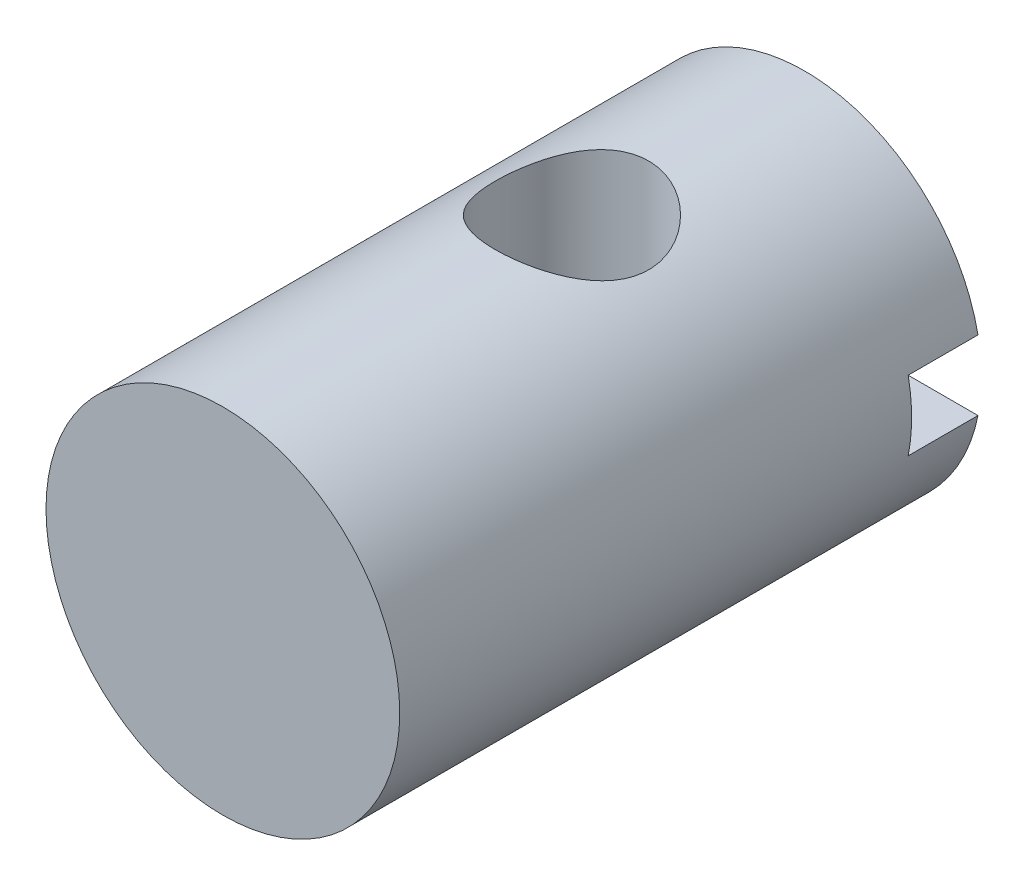
SolidWorks part; units mm, degrees
material "ABS"
ref_plane "Piano frontale" through (0, 0, 0) normal (0, 0, 1) x (1, 0, 0)
ref_plane "Piano superiore" through (0, 0, 0) normal (0, 1, 0) x (1, 0, 0)
ref_plane "Piano destro" through (0, 0, 0) normal (1, 0, 0) x (0, 0, -1)
ref_plane "Piano1" through (0, 0, 0) normal (0, -1, 0) x (1, 0, 0)
sketch "Schizzo1" plane through (0, 0, 0) normal (0, -1, 0) x (1, 0, 0)
  line L0 (13.8, -1.5) -> (10, -1.5)
  line L1 (10, -1.5) -> (10, -14)
  line L2 (10, -14) -> (13.8, -14)
  line L3 (13.8, -14) -> (13.8, -1.5)
  line L4 (10, -1.5) -> (10, -14) construction
  dimension "D1" = 3.8
  dimension "D2" = 12.5
revolve "Rivoluzione1" add sketch "Schizzo1" angle 360 about L4
sketch "Schizzo2" plane through (0, 0, -14) normal (0, 0, -1) x (-1, 0, 0)
  line L0 (-13.7253, -0.75) -> (-6.2747, -0.75)
  arc A0 (-6.2747, -0.75) -> (-13.7253, -0.75) centre (-10, 0) ccw
  circle A1 centre (-10, 0) radius 3.8 construction
  dimension "D1" = 3.8
  dimension "D2" = 3.7253
  dimension "D3" = 3.7253
  dimension "D4" = 0.75
extrude "Taglio-Estrusione1" cut sketch "Schizzo2" against normal blind 1.5
sketch "Schizzo3" plane through (0, 0, -12.5) normal (0, 0, -1) x (-1, 0, 0)
  line L0 (-6.2747, 0.75) -> (-13.7253, 0.75)
  arc A0 (-13.7253, 0.75) -> (-6.2747, 0.75) centre (-10, 0) cw
  dimension "D1" = 3.8
  dimension "D2" = 3.7253
  dimension "D3" = 0.75
extrude "Estrusione-Estrusione1" add sketch "Schizzo3" along normal blind 1.5
hole_wizard "Foro Ø3.3 (3.3)-1" positions "Schizzo3D1" profile "Schizzo4" hole size "Ø3.3" standard "Ansi Metric"
sketch3d "Schizzo3D1"
  point P0 (10, 3.8, -9)
sketch "Schizzo4" plane through (10, 3.8, -9) normal (1, 0, 0) x (0, 0, 1)
  line L0 (0, 0) -> (0, 7.6)
  line L1 (0, 7.6) -> (1.65, 7.6)
  line L2 (1.65, 7.6) -> (1.65, 0)
  line L5 (1.65, 0) -> (0, 0)
  line L11 (0, -6.35) -> (0, 107.95) construction
  dimension "Thru Hole Dia." = 3.3
  dimension "Thru Hole Depth" = 7.6
